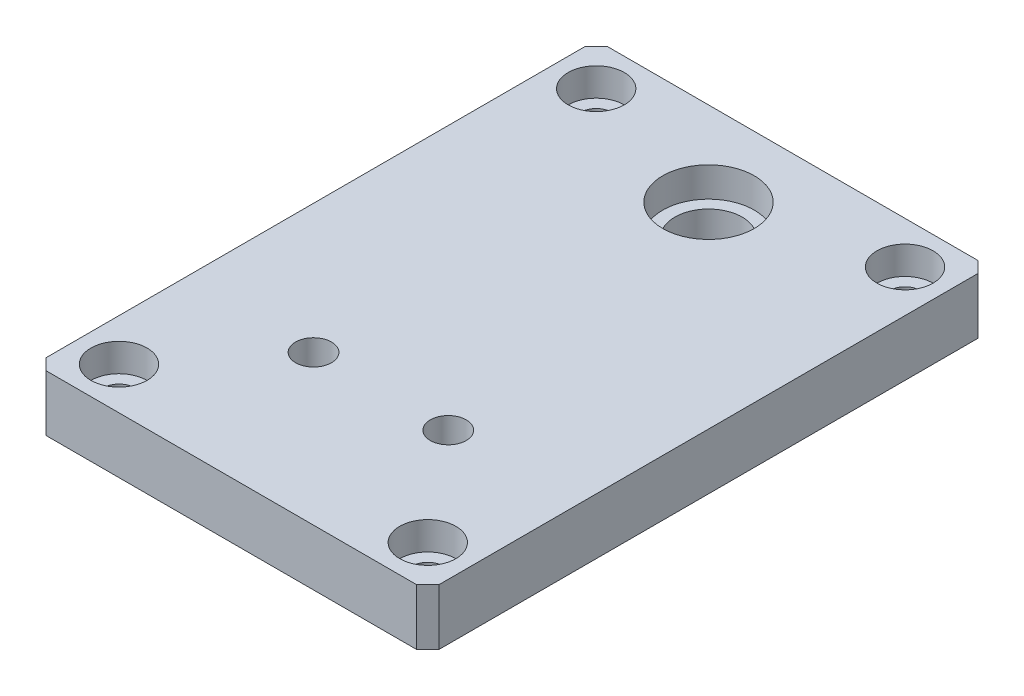
SolidWorks part; units mm, degrees
ref_plane "Front Plane" through (0, 0, 0) normal (0, 0, 1) x (1, 0, 0)
ref_plane "Top Plane" through (0, 0, 0) normal (0, 1, 0) x (1, 0, 0)
ref_plane "Right Plane" through (0, 0, 0) normal (1, 0, 0) x (0, 0, -1)
sketch "Sketch1" plane through (0, 0, 0) normal (0, 1, 0) x (1, 0, 0)
  line L1 (-35, -50) -> (35, -50)
  line L2 (-35, -50) -> (-35, 50)
  line L3 (-35, 50) -> (35, 50)
  line L4 (35, -50) -> (35, 50)
  line L5 (-35, -50) -> (35, 50) construction
  line L6 (-35, 50) -> (35, -50) construction
  point P0 (0, 0)
  dimension "D1" = 70
  dimension "D2" = 100
extrude "Boss-Extrude1" add sketch "Sketch1" along normal blind 10
sketch "Sketch4" plane through (0, 10, 0) normal (0, 1, 0) x (1, 0, 0)
  line L0 (-35, 50) -> (-35, -50) construction
  line L1 (35, 50) -> (-35, 50) construction
  line L3 (35, -50) -> (35, 50) construction
  line L4 (-35, -50) -> (35, -50) construction
  point P0 (-27.5, -42.5)
  point P2 (-27.5, 42.5)
  point P4 (27.5, 42.5)
  point P6 (27.5, -42.5)
  dimension "D1" = 7.5
  dimension "D2" = 7.5
  dimension "D3" = 7.5
  dimension "D4" = 7.5
hole_wizard "CBORE for M5 SHCS1" positions "Sketch4" profile "Sketch3" counterbore size "M5" standard "ANSI Metric" end condition through all
sketch "Sketch3" plane through (-27.5, 10, 42.5) normal (1, 0, 0) x (0, 0, 1)
  line L0 (0, 0) -> (0, 10)
  line L1 (0, 10) -> (2.75, 10)
  line L3 (2.75, 10) -> (2.75, 5)
  line L4 (2.75, 5) -> (5, 5)
  line L5 (5, 5) -> (5, 0)
  line L7 (5, 0) -> (0, 0)
  line L11 (0, -6.35) -> (0, 107.95) construction
  dimension "Thru Hole Dia." = 5.5
  dimension "Thru Hole Depth" = 10
  dimension "C'Bore Dia." = 10
  dimension "C'Bore Depth" = 5
sketch "Sketch7" plane through (0, 10, 0) normal (0, 1, 0) x (1, 0, 0)
  line L0 (35, 50) -> (-35, 50) construction
  point P0 (0, 35)
  dimension "D1" = 15
hole_wizard "Ø1.0mm Dowel Hole1" positions "Sketch7" profile "Sketch6" hole size "Ø1.0" standard "ANSI Metric"
sketch "Sketch6" plane through (0, 10, -35) normal (1, 0, 0) x (0, 0, 1)
  line L0 (0, 0) -> (0, 5.3)
  line L1 (0, 5.3) -> (8.15, 5.3)
  line L2 (8.15, 5.3) -> (8.15, 0)
  line L5 (8.15, 0) -> (0, 0)
  line L10 (0, 5.3) -> (-8.15, 5.3) construction
  line L11 (0, -6.35) -> (0, 107.95) construction
  dimension "Hole Dia." = 16.3
  dimension "Hole Depth" = 5.3
  dimension "Drill Angle" = 180
sketch "Sketch13" plane through (0, 4.7, 0) normal (0, 1, 0) x (1, 0, 0)
  point P0 (0, 35)
hole_wizard "Ø1.0mm Dowel Hole3" positions "Sketch13" profile "Sketch12" hole size "Ø1.0" standard "ANSI Metric" end condition through all
sketch "Sketch12" plane through (0, 4.7, -35) normal (1, 0, 0) x (0, 0, 1)
  line L0 (0, 0) -> (0, 4.7)
  line L1 (0, 4.7) -> (6, 4.7)
  line L2 (6, 4.7) -> (6, 0)
  line L5 (6, 0) -> (0, 0)
  line L11 (0, -6.35) -> (0, 107.95) construction
  dimension "Thru Hole Dia." = 12
  dimension "Thru Hole Depth" = 4.7
sketch "Sketch14" plane through (0, 10, 0) normal (0, 1, 0) x (1, 0, 0)
  circle A2 centre (12, -23.35) radius 3.2
  circle A3 centre (-12, -23.35) radius 3.2
  dimension "D5" = 6.4
  dimension "D6" = 6.4
  dimension "D1" = 23.35
  dimension "D2" = 12
  dimension "D3" = 12
  dimension "D4" = 23.35
extrude "Cut-Extrude1" cut sketch "Sketch14" against normal through all
chamfer "Chamfer1" distance 2 angle 45 4 edges at (35, 5, 50) (35, 5, -50) (-35, 5, -50) (-35, 5, 50)
equation "\"D1@Sketch4\" = 5 * 1.5"
equation "\"D2@Sketch4\" = \"D1@Sketch4\""
